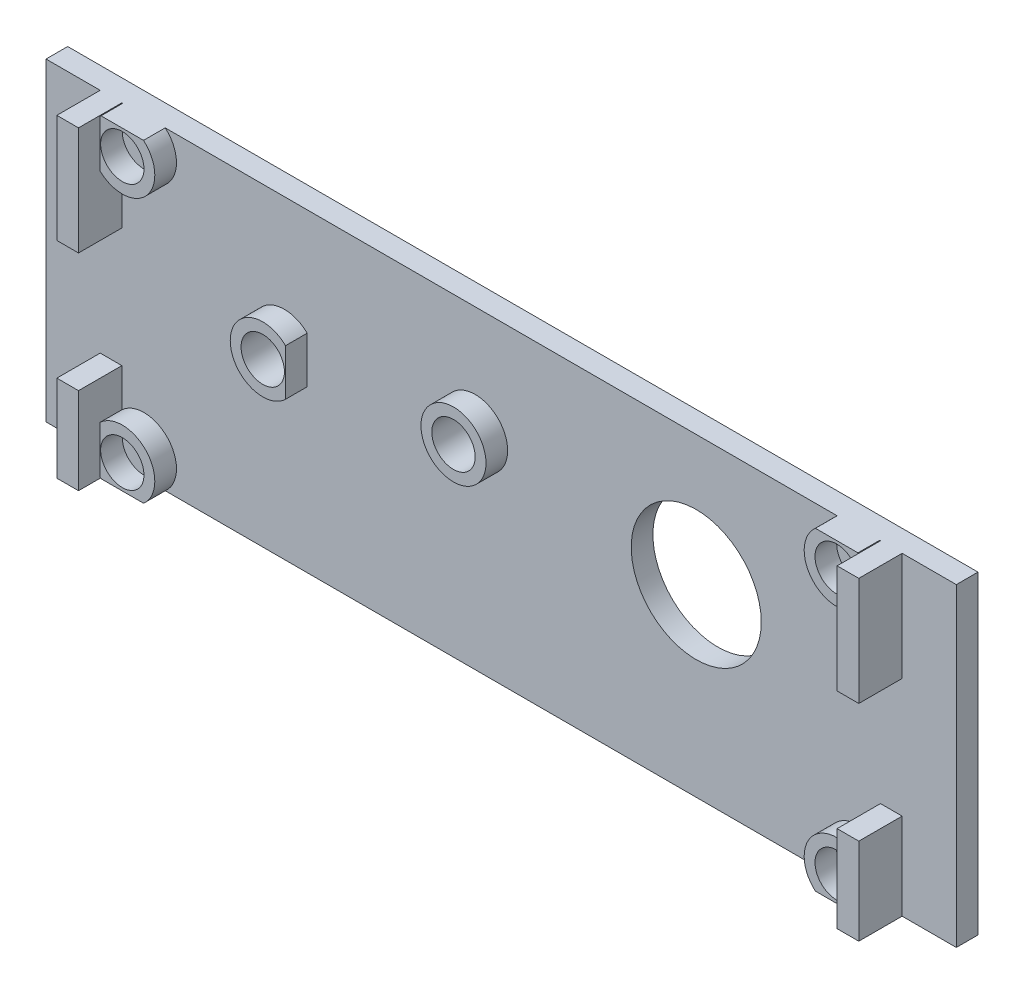
SolidWorks part; units mm, degrees
material "ABS PC"
ref_plane "Piano frontale" through (0, 0, 0) normal (0, 0, 1) x (1, 0, 0)
ref_plane "Piano superiore" through (0, 0, 0) normal (0, 1, 0) x (1, 0, 0)
ref_plane "Piano destro" through (0, 0, 0) normal (1, 0, 0) x (0, 0, -1)
sketch "Schizzo2" plane through (0, 0, 0) normal (0, 0, 1) x (1, 0, 0)
  line L1 (-21, -7.25) -> (21, -7.25)
  line L2 (-21, -7.25) -> (-21, 7.25)
  line L3 (-21, 7.25) -> (21, 7.25)
  line L4 (21, -7.25) -> (21, 7.25)
  line L5 (-21, -7.25) -> (21, 7.25) construction
  line L6 (-21, 7.25) -> (21, -7.25) construction
  circle A0 centre (9, 1.25) radius 3
  circle A1 centre (-1.2, 2.25) radius 1
  circle A2 centre (-10, 1.25) radius 1
  point P0 (0, 0)
  dimension "D3" = 6
  dimension "D4" = 2
  dimension "D5" = 2
  dimension "D1" = 14.5
  dimension "D2" = 42
  dimension "D6" = 12
  dimension "D7" = 6
  dimension "D8" = 22.2
  dimension "D9" = 5
  dimension "D10" = 11
  dimension "D11" = 6
extrude "Estrusione-Estrusione1" add sketch "Schizzo2" along normal blind 1
sketch "Schizzo4" plane through (0, 0, 1) normal (0, 0, 1) x (1, 0, 0)
  line L0 (21, 7.25) -> (-21, 7.25) construction
  line L1 (17.5, 7.25) -> (18.5, 7.25)
  line L2 (17.5, 7.25) -> (17.5, 2.25)
  line L3 (17.5, 2.25) -> (18.5, 2.25)
  line L4 (18.5, 7.25) -> (18.5, 2.25)
  line L5 (21, -7.25) -> (21, 7.25) construction
  line L6 (-21, -7.25) -> (21, -7.25) construction
  line L7 (17.5, -7.25) -> (18.5, -7.25)
  line L8 (17.5, -7.25) -> (17.5, -3.25)
  line L9 (17.5, -3.25) -> (18.5, -3.25)
  line L10 (18.5, -7.25) -> (18.5, -3.25)
  line L11 (0, 0) -> (0, -3.2171) construction
  line L12 (-21, 7.25) -> (-21, -7.25) construction
  line L13 (-18.5, -3.25) -> (-17.5, -3.25)
  line L14 (-18.5, -3.25) -> (-18.5, -7.25)
  line L15 (-18.5, -7.25) -> (-17.5, -7.25)
  line L16 (-17.5, -3.25) -> (-17.5, -7.25)
  line L17 (-18.5, 7.25) -> (-17.5, 7.25)
  line L18 (-18.5, 7.25) -> (-18.5, 2.25)
  line L19 (-18.5, 2.25) -> (-17.5, 2.25)
  line L20 (-17.5, 7.25) -> (-17.5, 2.25)
  dimension "D1" = 1
  dimension "D2" = 2.5
  dimension "D3" = 5
  dimension "D4" = 1
  dimension "D5" = 2.5
  dimension "D6" = 4
  dimension "D7" = 1
  dimension "D8" = 2.5
  dimension "D9" = 4
  dimension "D10" = 1
  dimension "D11" = 2.5
  dimension "D12" = 5
extrude "Estrusione-Estrusione2" add sketch "Schizzo4" along normal blind 2
sketch "Schizzo5" plane through (0, 0, 1) normal (0, 0, 1) x (1, 0, 0)
  line L0 (17.5, 7.25) -> (-17.5, 7.25) construction
  line L1 (-17.5, 2.25) -> (-17.5, 7.25) construction
  line L3 (-17.5, 2.25) -> (-17.5, 7.25) construction
  line L4 (-17.5, 7.2142) -> (-17.5, 5.0146)
  line L5 (-17.46, 7.25) -> (-15.5, 7.25)
  line L6 (0, 0) -> (-2.8252, 0) construction
  line L7 (-17.46, -7.25) -> (-15.5, -7.25)
  line L8 (-17.5, -7.2142) -> (-17.5, -5.0146)
  line L9 (0, 0) -> (0, -2.1129) construction
  line L10 (17.46, -7.25) -> (15.5, -7.25)
  line L11 (17.5, -7.2142) -> (17.5, -5.0146)
  line L12 (17.46, 7.25) -> (15.5, 7.25)
  line L13 (17.5, 7.2142) -> (17.5, 5.0146)
  circle A0 centre (-1.2, 2.25) radius 1.5
  circle A1 centre (-10, 1.25) radius 1.5
  circle A2 centre (-16.48, 6.1144) radius 1
  arc A3 (-17.5, 5.0146) -> (-15.5, 7.25) centre (-16.48, 6.1144) ccw
  arc A4 (-17.46, 7.25) -> (-17.5, 7.2142) centre (-16.48, 6.1144) ccw
  arc A5 (-17.46, -7.25) -> (-17.5, -7.2142) centre (-16.48, -6.1144) cw
  arc A6 (-17.5, -5.0146) -> (-15.5, -7.25) centre (-16.48, -6.1144) cw
  circle A7 centre (-16.48, -6.1144) radius 1
  arc A8 (17.5, -5.0146) -> (15.5, -7.25) centre (16.48, -6.1144) ccw
  arc A9 (17.46, -7.25) -> (17.5, -7.2142) centre (16.48, -6.1144) ccw
  circle A10 centre (16.48, -6.1144) radius 1
  arc A11 (17.46, 7.25) -> (17.5, 7.2142) centre (16.48, 6.1144) cw
  arc A12 (17.5, 5.0146) -> (15.5, 7.25) centre (16.48, 6.1144) cw
  circle A13 centre (16.48, 6.1144) radius 1
  circle A14 centre (-10, 1.25) radius 1 construction
  circle A15 centre (-10, 1.25) radius 1
  circle A16 centre (-1.2, 2.25) radius 1 construction
  circle A17 centre (-1.2, 2.25) radius 1
  point P9 (-15.5, 7.25)
  dimension "D1" = 3
  dimension "D2" = 3
  dimension "D3" = 2
  dimension "D4" = 3
  dimension "D5" = 2
  dimension "D6" = 1.02
extrude "Estrusione-Estrusione3" add sketch "Schizzo5" along normal blind 1
sketch "Schizzo6" plane through (0, 0, 2) normal (0, 0, 1) x (1, 0, 0)
  line L0 (-8.9497, 2.3209) -> (-8.9497, 0.1791)
  circle A0 centre (-10, 1.25) radius 1.5 construction
  circle A1 centre (-10, 1.25) radius 1.5 construction
  arc A2 (-8.9497, 0.1791) -> (-8.9497, 2.3209) centre (-10, 1.25) ccw
  dimension "D1" = 1.0503
extrude "Taglio-Estrusione1" cut sketch "Schizzo6" against normal up to surface (1 mm away) up to face at (0, -0.1667, 1)
sketch "Schizzo7" plane through (0, 0, 0) normal (0, 0, -1) x (-1, 0, 0)
  line L0 (1.2, 3.75) -> (1.2, 0.75)
  arc A2 (1.2, 0.75) -> (1.2, 3.75) centre (1.2, 2.25) ccw
  circle A3 centre (1.2, 2.25) radius 1 construction
  circle A4 centre (10, 1.25) radius 1.5
  dimension "D1" = 3
  dimension "D2" = 3
extrude "Estrusione-Estrusione4" add sketch "Schizzo7" along normal blind 1
